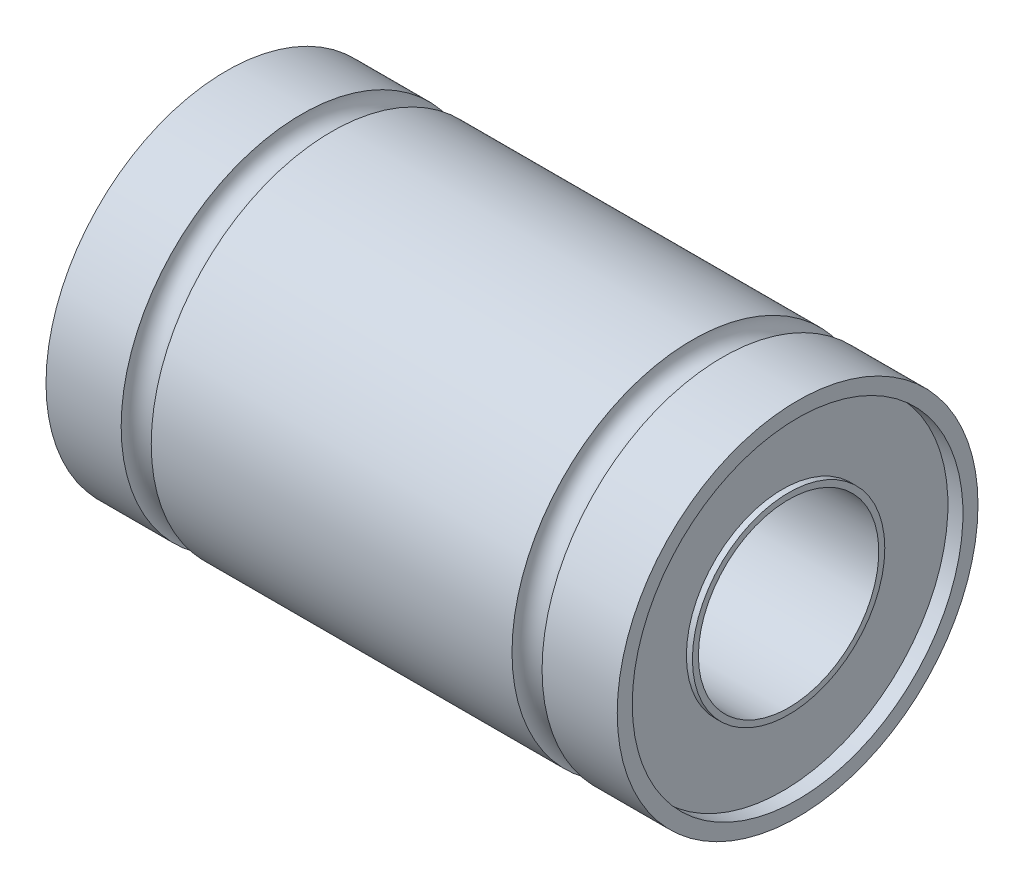
SolidWorks part; units mm, degrees
ref_plane "Front Plane" through (0, 0, 0) normal (0, 0, 1) x (1, 0, 0)
ref_plane "Top Plane" through (0, 0, 0) normal (0, 1, 0) x (1, 0, 0)
ref_plane "Right Plane" through (0, 0, 0) normal (1, 0, 0) x (0, 0, -1)
sketch "Sketch1" plane through (0, 0, 0) normal (0, 0, 1) x (1, 0, 0)
  line L0 (3.5, 6) -> (15.5, 6)
  line L1 (0.3, 3) -> (18.7, 3)
  line L2 (0, 5.5) -> (0, 6)
  line L3 (0, 6) -> (2.5, 6)
  line L5 (16.5, 6) -> (19, 6)
  line L6 (0, 5.5) -> (0.5, 5.5)
  line L7 (0.5, 5.5) -> (0.5, 3.2)
  line L8 (0.5, 3.2) -> (0.3, 3.2)
  line L9 (0.3, 3.2) -> (0.3, 3)
  line L10 (9.5, 6) -> (9.5, 3) construction
  line L11 (18.7, 3.2) -> (18.7, 3)
  line L12 (18.5, 3.2) -> (18.7, 3.2)
  line L13 (18.5, 5.5) -> (18.5, 3.2)
  line L14 (19, 5.5) -> (18.5, 5.5)
  line L15 (19, 5.5) -> (19, 6)
  arc A0 (2.5, 6) -> (3.5, 6) centre (3, 6) ccw
  arc A1 (15.5, 6) -> (16.5, 6) centre (16, 6) ccw
  dimension "D5" = 0.5
  dimension "D1" = 19
  dimension "D2" = 6
  dimension "D3" = 3
  dimension "D4" = 3
  dimension "D6" = 0
  dimension "D7" = 0.5
  dimension "D8" = 0.2
  dimension "D9" = 0.2
  dimension "D10" = 0.5
ref_axis "Axis1" through (-0.95, 0, 0) along (1, 0, 0)
revolve "Revolve3" add sketch "Sketch1" angle 360 about axis through (-0.95, 0, 0) along (1, 0, 0)
